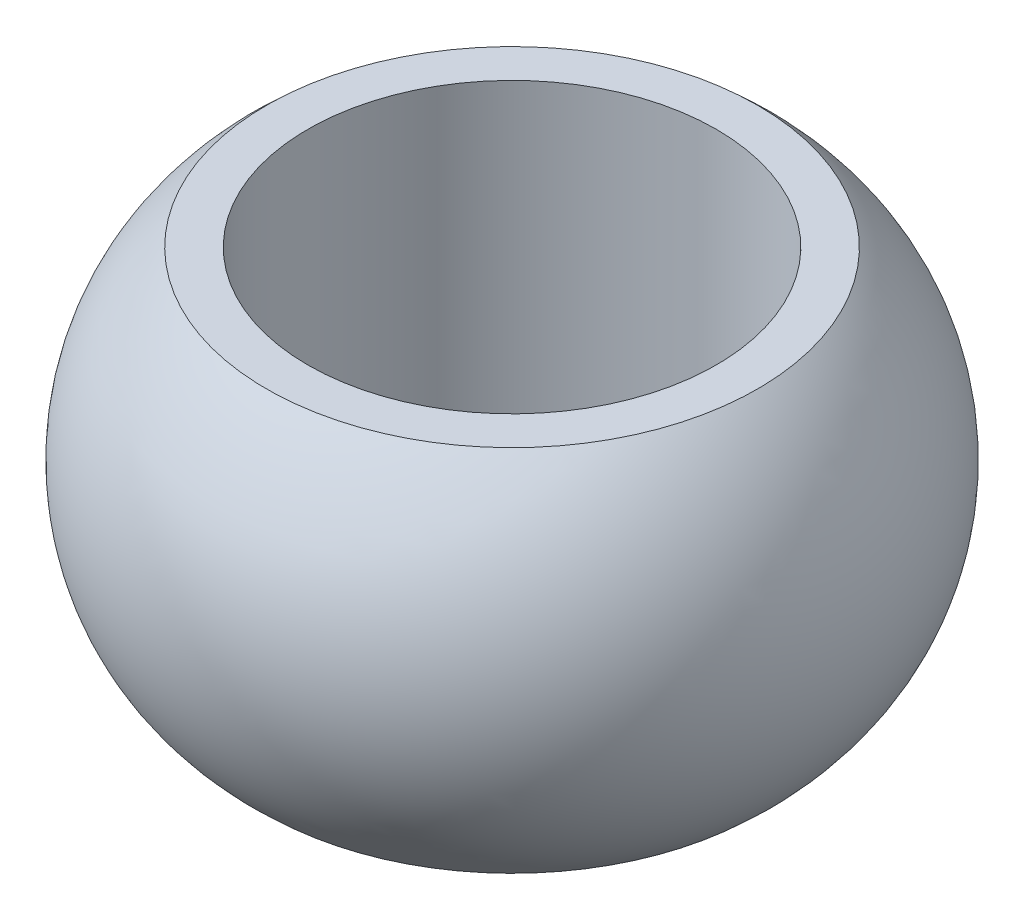
SolidWorks part; units mm, degrees
material "Chrome Stainless Steel"
ref_plane "Front Plane" through (0, 0, 0) normal (0, 0, 1) x (1, 0, 0)
ref_plane "Top Plane" through (0, 0, 0) normal (0, 1, 0) x (1, 0, 0)
ref_plane "Right Plane" through (0, 0, 0) normal (1, 0, 0) x (0, 0, -1)
sketch "Sketch1" plane through (0, 0, 0) normal (0, 0, 1) x (1, 0, 0)
  line L0 (0, 0) -> (0, 74.6658) construction
  line L1 (4.93, -4.45) -> (4.93, 4.45)
  line L2 (4.93, 4.45) -> (5.93, 4.45)
  line L3 (4.93, -4.45) -> (5.93, -4.45)
  arc A0 (5.93, 4.45) -> (5.93, -4.45) centre (2.0675, 0) cw
  point P9 (4.93, 0)
  dimension "D3" = 15.92
  dimension "D4" = 1
  dimension "D1" = 9.86
  dimension "D2" = 8.9
revolve "Revolve1" add sketch "Sketch1" angle 360 about L0
